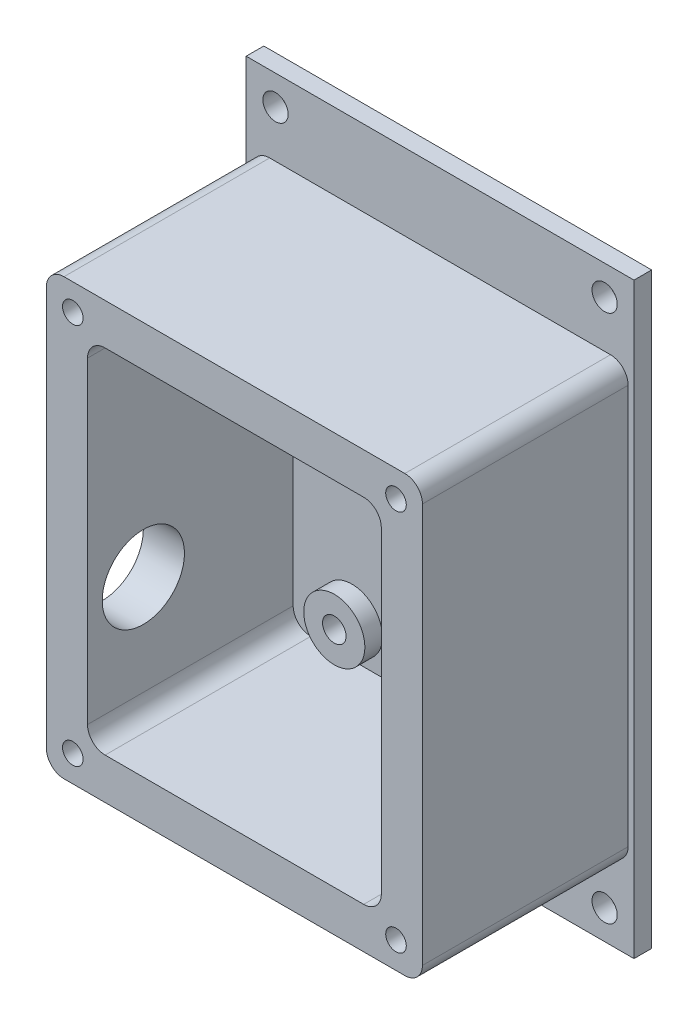
SolidWorks part; units mm, degrees
ref_plane "Přední rovina" through (0, 0, 0) normal (0, 0, 1) x (1, 0, 0)
ref_plane "Horní rovina" through (0, 0, 0) normal (0, 1, 0) x (1, 0, 0)
ref_plane "Pravá rovina" through (0, 0, 0) normal (1, 0, 0) x (0, 0, -1)
sketch "Skica1" plane through (0, 0, 0) normal (0, 0, 1) x (1, 0, 0)
  line L1 (0, 0) -> (50, 0)
  line L2 (0, 0) -> (0, 60)
  line L3 (0, 60) -> (50, 60)
  line L4 (50, 0) -> (50, 60)
  dimension "D1" = 60
  dimension "D2" = 50
extrude "Přidat vysunutím2" add sketch "Skica1" along normal blind 3 contours L3 L4 L1 L2
sketch "Skica2" plane through (0, 0, 3) normal (0, 0, 1) x (1, 0, 0)
  line L0 (0, 60) -> (50, 60) construction
  line L1 (0, 0) -> (0, 60) construction
  line L2 (10, 54.5) -> (36, 54.5) construction
  line L3 (50, 0) -> (50, 60) construction
  line L5 (10, 6) -> (10, 54.5) construction
  line L6 (10, 54.5) -> (36, 54.5) construction
  line L7 (36, 54.5) -> (36, 6) construction
  line L8 (36, 6) -> (10, 6) construction
  line L9 (0, 0) -> (50, 0) construction
  line L10 (10, 6) -> (0, 6) construction
  circle A0 centre (10, 54.5) radius 2
  circle A1 centre (36, 54.5) radius 2
  circle A2 centre (36, 6) radius 2
  circle A3 centre (10, 6) radius 2
  point P18 (9, 56.9985)
  point P20 (9, 4.021)
  dimension "D1" = 4
  dimension "D9" = 6
  dimension "D2" = 5.5
  dimension "D3" = 10
  dimension "D6" = 26
  dimension "D7" = 14
  dimension "D8" = 48.5
  dimension "D10" = 10
  dimension "D4" = 2
  dimension "D5" = 2
sketch "Skica3" plane through (0, 0, 3) normal (0, 0, 1) x (1, 0, 0)
  line L3 (0, 0) -> (50, 0) construction
  line L4 (0, 60) -> (50, 60) construction
  line L5 (0, 0) -> (0, 60) construction
  line L6 (50, 0) -> (50, 60) construction
  line L11 (0, 60) -> (50, 60)
  line L12 (0, 60) -> (0, 0)
  line L13 (0, 0) -> (50, 0)
  line L14 (50, 60) -> (50, 0)
extrude "Vysunout tenkostěnný1" add sketch "Skica3" along normal blind 35 separate body thin thin type one direction wall 7
sketch "Skica4" plane through (0, 0, 0) normal (0, 0, -1) x (-1, 0, 0)
  line L8 (-53, 75) -> (3, 75) construction
  line L9 (0, 60) -> (-50, 60) construction
  line L10 (7, 67) -> (7, -7) construction
  line L11 (8, 80) -> (8, -20)
  line L12 (-58, -20) -> (8, -20)
  line L13 (-58, 80) -> (-58, -20)
  line L14 (-58, 80) -> (8, 80)
  line L16 (-50, 60) -> (0, 60)
  line L17 (-50, 60) -> (-50, 0)
  line L18 (-50, 0) -> (0, 0)
  line L19 (0, 60) -> (0, 0)
  line L21 (0, 0) -> (-50, 0) construction
  line L22 (-50, 0) -> (-50, 60) construction
  line L23 (-57, -7) -> (-57, 67) construction
  circle A0 centre (-53, 75) radius 2.15
  circle A1 centre (3, 75) radius 2.15
  circle A2 centre (3, -15) radius 2.15
  circle A3 centre (-53, -15) radius 2.15
  dimension "D2" = 4.3
  dimension "D9" = 20
  dimension "D10" = 5
  dimension "D11" = 5
  dimension "D7" = 5
  dimension "D12" = 1
  dimension "D3" = 5
  dimension "D4" = 5
  dimension "D8" = 20
  dimension "D14" = 1
  dimension "D5" = 2
  dimension "D6" = 2
extrude "Přidat vysunutím5" add sketch "Skica4" against normal blind 3
extrude "Vysunout tenkostěnný2" add sketch "Skica2" along normal blind 3 thin
fillet "Zaoblit2" radius 3 4 edges at (-7, -7, 20.5) (57, -7, 20.5) (57, 67, 20.5) (-7, 67, 20.5)
sketch "Skica9" plane through (0, 0, 0) normal (1, 0, 0) x (0, 0, -1)
  line L0 (-3, 60) -> (-3, 0) construction
  circle A0 centre (-28.5, 20) radius 7
  dimension "D1" = 14
  dimension "D2" = 25.5
extrude "Odebrat vysunutím3" cut sketch "Skica9" against normal up to next
sketch "Skica10" plane through (0, 0, 38) normal (0, 0, 1) x (1, 0, 0)
  line L0 (-2.5, 62.5) -> (52.5, 62.5) construction
  line L1 (-2.5, 62.5) -> (-2.5, -2.5) construction
  line L3 (54, 67) -> (-4, 67) construction
  line L4 (57, -4) -> (57, 64) construction
  circle A0 centre (-2.5, 62.5) radius 1.75
  circle A1 centre (52.5, 62.5) radius 1.75
  circle A2 centre (52.5, -2.5) radius 1.75
  circle A3 centre (-2.5, -2.5) radius 1.75
  dimension "D5" = 3.5
  dimension "D3" = 55
  dimension "D4" = 65
  dimension "D6" = 4.5
  dimension "D7" = 4.5
  dimension "D1" = 2
  dimension "D2" = 2
fillet "Zaoblit4" radius 3 1 edges at (50, 60, 20.5)
fillet "Zaoblit5" radius 3 1 edges at (50, 0, 20.5)
fillet "Zaoblit6" radius 3 1 edges at (0, 0, 20.5)
fillet "Zaoblit7" radius 3 1 edges at (0, 60, 20.5)
extrude "Odebrat vysunutím4" cut sketch "Skica10" against normal blind 5
